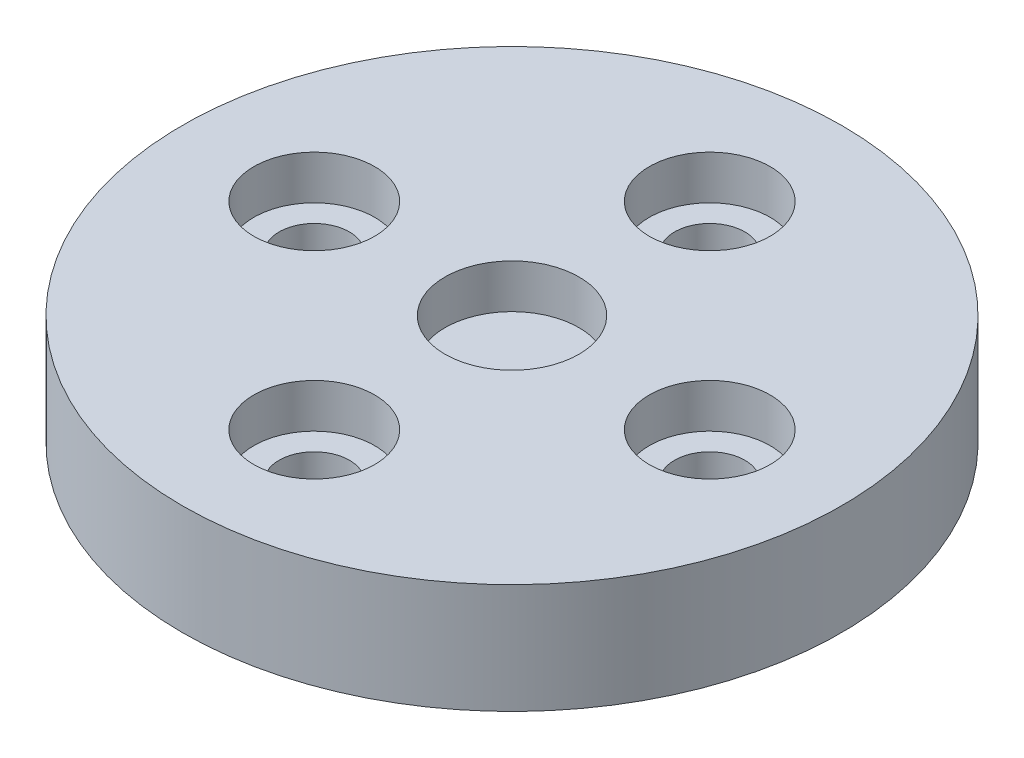
SolidWorks part; units mm, degrees
ref_plane "Front Plane" through (0, 0, 0) normal (0, 0, 1) x (1, 0, 0)
ref_plane "Top Plane" through (0, 0, 0) normal (0, 1, 0) x (1, 0, 0)
ref_plane "Right Plane" through (0, 0, 0) normal (1, 0, 0) x (0, 0, -1)
sketch "Sketch1" plane through (0, 0, 0) normal (0, 1, 0) x (1, 0, 0)
  circle A0 centre (0, 0) radius 15
  dimension "D1" = 30
extrude "Boss-Extrude1" add sketch "Sketch1" along normal blind 5
sketch "Sketch2" plane through (0, 0, 0) normal (0, -1, 0) x (1, 0, 0)
  circle A0 centre (0, 0) radius 3
  dimension "D1" = 6
extrude "Cut-Extrude1" cut sketch "Sketch2" against normal blind 2
sketch "Sketch3" plane through (0, 5, 0) normal (0, 1, 0) x (1, 0, 0)
  line L0 (-1000, 0) -> (49000, 0) construction
  line L1 (0, -1000) -> (0, 49000) construction
  line L2 (0, 0) -> (35355.3391, 35355.3391) construction
  circle A0 centre (0, 0) radius 9 construction
  circle A1 centre (0, 9) radius 1.6
  circle A2 centre (0, -9) radius 1.6
  circle A3 centre (9, 0) radius 1.6
  circle A4 centre (-9, 0) radius 1.6
  dimension "D1" = 18
  dimension "D2" = 3.2
extrude "Cut-Extrude2" cut sketch "Sketch3" against normal up to surface (5 mm away) up to face at (0, 0, -3)
sketch "Sketch4" plane through (0, 5, 0) normal (0, 1, 0) x (1, 0, 0)
  circle A0 centre (0, 9) radius 2.75
  circle A1 centre (-9, 0) radius 2.75
  circle A2 centre (9, 0) radius 2.75
  circle A3 centre (0, -9) radius 2.75
  circle A4 centre (0, 0) radius 3.05
  dimension "D1" = 5.5
  dimension "D2" = 6.1
extrude "Cut-Extrude3" cut sketch "Sketch4" against normal blind 2
